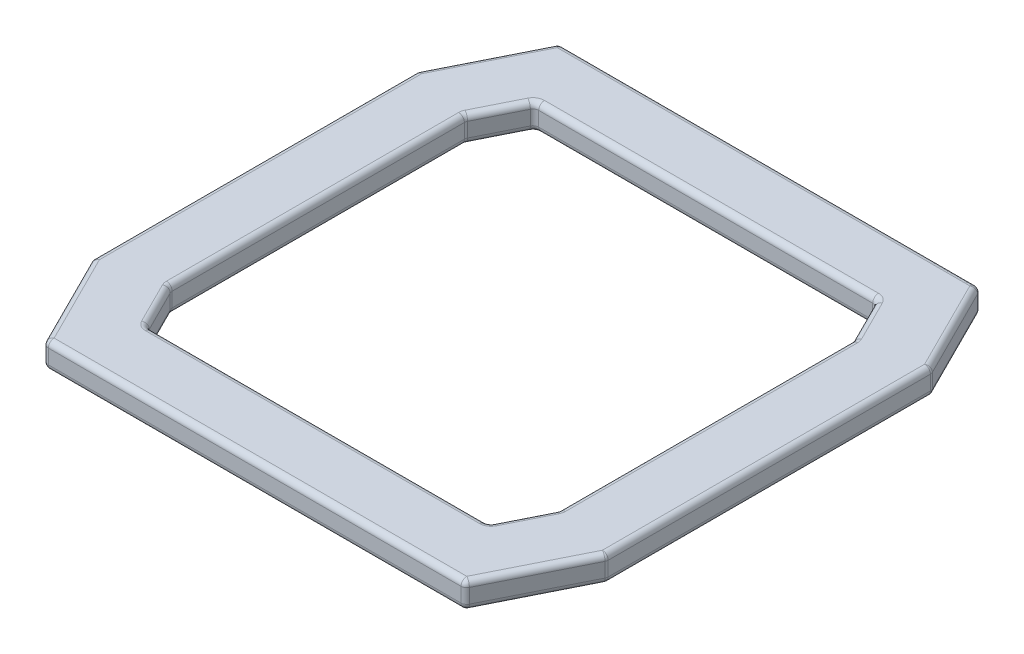
SolidWorks part; units mm, degrees
material "Copper"
ref_plane "Front Plane" through (0, 0, 0) normal (0, 0, 1) x (1, 0, 0)
ref_plane "Top Plane" through (0, 0, 0) normal (0, 1, 0) x (1, 0, 0)
ref_plane "Right Plane" through (0, 0, 0) normal (1, 0, 0) x (0, 0, -1)
sketch "Sketch1" plane through (0, 0, 0) normal (0, 1, 0) x (1, 0, 0)
  line L1 (-29.5, -33.5) -> (29.5, -33.5)
  line L2 (-33.5, -25.5) -> (-33.5, 25.5)
  line L4 (33.5, -25.5) -> (33.5, 25.5)
  line L5 (44.5, 0) -> (0, 0) construction
  line L6 (0, 0) -> (0, 44.5) construction
  line L7 (33.5, 25.5) -> (29.5, 33.5)
  line L8 (29.5, -33.5) -> (33.5, -25.5)
  line L9 (-33.5, -25.5) -> (-29.5, -33.5)
  line L10 (-29.5, 33.5) -> (-33.5, 25.5)
  line L11 (29.5, 33.5) -> (-29.5, 33.5)
  line L29 (-36.2984, -44.5) -> (36.2984, -44.5)
  line L30 (36.2984, -44.5) -> (44.5, -28.0967)
  line L31 (44.5, -28.0967) -> (44.5, 28.0967)
  line L32 (44.5, 28.0967) -> (36.2984, 44.5)
  line L33 (36.2984, 44.5) -> (-36.2984, 44.5)
  line L34 (-36.2984, 44.5) -> (-44.5, 28.0967)
  line L35 (-44.5, -28.0967) -> (-44.5, 28.0967)
  line L36 (-44.5, -28.0967) -> (-36.2984, -44.5)
  point P4 (0, 0)
  point P9 (0, 0)
  dimension "D1" = 67
  dimension "D4" = 8
  dimension "D2" = 4
  dimension "D5" = 4
  dimension "D8" = 4
  dimension "D9" = 8
  dimension "D7" = 4
  dimension "D3" = 8
  dimension "D10" = 8
  dimension "D12" = 67
  dimension "D6" = 11
extrude "Boss-Extrude1" add sketch "Sketch1" along normal mid plane 4.5
fillet "Fillet1" radius 1 48 edges at (29.5, 0, -33.5) (33.5, 0, -25.5) (-33.5, 0, -25.5) (-29.5, 0, -33.5) (-29.5, 0, 33.5) (-33.5, 0, 25.5) (33.5, 0, 25.5) (29.5, 0, 33.5) (36.2984, 0, 44.5) (44.5, 0, 28.0967) (-44.5, 0, 28.0967) (-36.2984, 0, 44.5) (-36.2984, 0, -44.5) (-44.5, 0, -28.0967) (44.5, 0, -28.0967) (36.2984, 0, -44.5) (33.5, -2.25, 0) (31.5, -2.25, 29.5) (0, -2.25, 33.5) (-31.5, -2.25, 29.5) (-33.5, -2.25, 0) (-31.5, -2.25, -29.5) (0, -2.25, -33.5) (31.5, -2.25, -29.5) (0, -2.25, 44.5) (40.3992, -2.25, 36.2984) (44.5, -2.25, 0) (40.3992, -2.25, -36.2984) (0, -2.25, -44.5) (-40.3992, -2.25, -36.2984) (-44.5, -2.25, 0) (-40.3992, -2.25, 36.2984) (-31.5, 2.25, -29.5) (-33.5, 2.25, 0) (-31.5, 2.25, 29.5) (0, 2.25, 33.5) (31.5, 2.25, 29.5) (33.5, 2.25, 0) (31.5, 2.25, -29.5) (0, 2.25, -33.5) (-44.5, 2.25, 0) (-40.3992, 2.25, -36.2984) (0, 2.25, -44.5) (40.3992, 2.25, -36.2984) (44.5, 2.25, 0) (40.3992, 2.25, 36.2984) (0, 2.25, 44.5) (-40.3992, 2.25, 36.2984)
